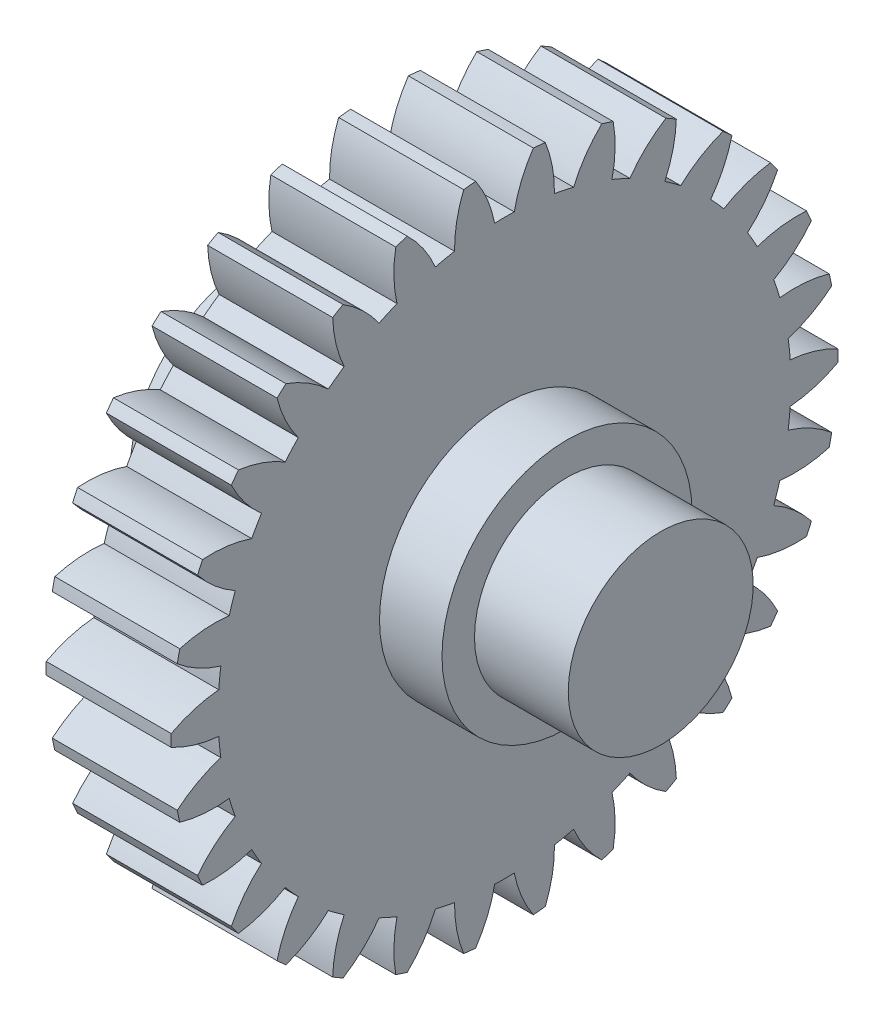
SolidWorks part; units mm, degrees
ref_plane "Plane1" through (0, 0, 0) normal (0, 0, 1) x (1, 0, 0)
ref_plane "Plane2" through (0, 0, 0) normal (0, 1, 0) x (1, 0, 0)
ref_plane "Plane3" through (0, 0, 0) normal (1, 0, 0) x (0, 0, -1)
other "Configuration Table"
sketch "HoldingSke" plane through (0, 0, 0) normal (0, 1, 0) x (1, 0, 0)
  line L0 (0, 0) -> (263.9645, -152.4)
  line L1 (-15, 0) -> (100, 0) construction
  line L2 (0, 0) -> (-2.1039, 2.3779)
  line L3 (0, 0) -> (-11.863, 4.5341)
  line L4 (0, 0) -> (7.479, 4.318)
  line L5 (0, 0) -> (-47.5972, -17.7524)
  line L6 (0, 0) -> (-10.5278, -7.1032)
  line L7 (-2.1039, 2.3779) -> (8.8311, 51.9884)
  line L8 (-76.2, 54.61) -> (-54.9402, 54.61)
  line L9 (-71.009, 38.7566) -> (-53.1078, 45.2721)
  line L10 (-76.2, 71.12) -> (104.1128, 71.12)
  line L11 (0, 0) -> (-12.7, 0)
  line L12 (-76.2, 101.6) -> (-76.1147, 101.6)
  line L13 (24.9733, 27.94) -> (52.9518, 28.4284)
  line L14 (24.9733, 27.94) -> (24.9746, 27.94)
  line L15 (24.9733, 27.94) -> (100.4006, 29.5858)
  circle A0 centre (0, 0) radius 9.525
  circle A1 centre (0, 0) radius 29.1029
  circle A2 centre (0, 0) radius 38.1
  circle A3 centre (0, 0) radius 9.525
  dimension "MHD" = 58.2058
  dimension "Hub_dia" = 76.2
  dimension "Bore" = 19.05
  dimension "MBD" = 19.05
  dimension "Num_teeth" = 30
  dimension "Pitch" = 304.8
  dimension "Overall_len" = 50.8
  dimension "Show_teeth" = 30
  dimension "Thickness" = 12.7
  dimension "OAL" = 50.8014
  dimension "T_dim" = 21.2598
  dimension "Ap" = 20
  dimension "H" = 19.05
  dimension "Pitch_radius" = 180.3128
  dimension "Width" = 12.7
  dimension "Backlash" = 0.0853
  dimension "Addendum_fac" = 1
  dimension "Dedendum_fac" = 1.25
  dimension "Clearance_fac" = 0.25
  dimension "Dedendum_add" = 0.0013
sketch "BasProSke" plane through (0, 0, 0) normal (0, 1, 0) x (1, 0, 0)
  line L0 (-10, 0) -> (60, 0) construction
  line L1 (0, 0) -> (0, 33.8667)
  line L2 (0, 0) -> (12.7, 0)
  line L3 (12.7, 0) -> (12.7, 33.8667)
  line L4 (12.7, 33.8667) -> (0, 33.8667)
  dimension "Thickness" = 12.7
  dimension "Diameter" = 67.7333
revolve "Base-Revolve" add sketch "BasProSke" angle 360 about L0
sketch "TooCutSke" plane through (0, 0, 0) normal (1, 0, 0) x (0, 0, -1)
  line L1 (0, 0) -> (0, 107) construction
  line L2 (0, 0) -> (-1.811, 31.6983) construction
  line L3 (0, 0) -> (-6.63, 63.0805) construction
  line L4 (-1.811, 31.6983) -> (-3.315, 31.5402) construction
  arc A0 (0.9953, 29.0859) -> (-0.9953, 29.0859) centre (0, 0) ccw
  arc A1 (2.9488, 33.7635) -> (-2.9488, 33.7635) centre (0, 0) ccw
  circle A2 centre (0, 0) radius 31.75 construction
  circle A3 centre (0, 0) radius 29.8352 construction
  arc A4 (-0.9953, 29.0859) -> (-2.9488, 33.7635) centre (-13.4553, 26.6289) ccw
  arc A5 (2.9488, 33.7635) -> (0.9953, 29.0859) centre (13.4553, 26.6289) ccw
  dimension "Root_dia" = 58.2058
  dimension "Overcut_dia" = 67.7841
  dimension "Pitch_dia" = 63.5
  dimension "Base_dia" = 59.6705
  dimension "Flank_rad" = 12.7
  dimension "Half_ang" = 6
  dimension "Half_CT" = 1.5123
extrude "ToothCut" cut sketch "TooCutSke" along normal through all
fillet "Breaks" [suppressed] radius 0.0423
fillet "RootFillets" [suppressed] radius 0.5304
pattern_circular "TeethCuts" count 30 every 12 about axis through (-10, 0, 0) along (1, 0, 0) of "ToothCut", "RootFillets", "Breaks"
sketch "HubNeaOneSke" plane through (0, 0, 0) normal (-1, 0, 0) x (0, 0, 1)
  circle A0 centre (0, 0) radius 29.1029
  dimension "Diameter" = 58.2058
extrude "HubNearOne" [suppressed] add sketch "HubNeaOneSke" along normal blind 38.1014
sketch "HubNeaBotSke" plane through (0, 0, 0) normal (-1, 0, 0) x (0, 0, 1)
  circle A0 centre (0, 0) radius 29.1029
  dimension "Diameter" = 58.2058
extrude "HubNearBoth" [suppressed] add sketch "HubNeaBotSke" along normal blind 19.0507
ref_plane "FarPln" through (12.7, 0, 0) normal (1, 0, 0) x (0, 0, -1)
sketch "HubFarSke" plane through (12.7, 0, 0) normal (1, 0, 0) x (0, 0, -1)
  circle A0 centre (0, 0) radius 29.1029
  dimension "Diameter" = 58.2058
extrude "HubFar" [suppressed] add sketch "HubFarSke" along normal blind 19.0507
sketch "Sketch1" plane through (0, 0, 0) normal (-1, 0, 0) x (0, 0, 1)
  circle A0 centre (0, 0) radius 12.7
  circle A1 centre (0, 0) radius 4.953
  dimension "D1" = 9.906
  dimension "D2" = 25.4
extrude "Boss-Extrude2" add sketch "Sketch1" along normal blind 12.7
sketch "Sketch3" plane through (0, 0, 0) normal (0, 1, 0) x (1, 0, 0)
  line L0 (0, 0.9953) -> (0, -0.9953) construction
  line L2 (-12.7, 0) -> (0, 0) construction
  circle A0 centre (-6.35, 0) radius 3.302
  dimension "D1" = 6.604
  dimension "D2" = 6.35
extrude "Cut-Extrude1" cut sketch "Sketch3" along normal through all
sketch "Sketch4" plane through (0, 0, 0) normal (0, 1, 0) x (1, 0, 0)
  line L1 (-3.527, 4.8895) -> (-9.173, 4.8895)
  line L2 (-9.173, 4.8895) -> (-11.9959, 0)
  line L3 (-11.9959, 0) -> (-9.173, -4.8895)
  line L4 (-9.173, -4.8895) -> (-3.527, -4.8895)
  line L5 (-3.527, -4.8895) -> (-0.7041, 0)
  line L6 (-0.7041, 0) -> (-3.527, 4.8895)
  line L7 (0, 12.7) -> (-12.7, 12.7) construction
  circle A0 centre (-6.35, 0) radius 4.8895 construction
  dimension "D1" = 9.779
extrude "Cut-Extrude2" cut sketch "Sketch4" along normal blind 8.255 contours L3 L4 L5 L6 L1 L2
sketch "Sketch5" plane through (12.7, 0, 0) normal (1, 0, 0) x (0, 0, -1)
  circle A0 centre (0, 0) radius 12.7
  dimension "D1" = 25.4
extrude "Boss-Extrude3" add sketch "Sketch5" along normal blind 6.35
sketch "Sketch6" plane through (19.05, 0, 0) normal (1, 0, 0) x (0, 0, -1)
  circle A0 centre (0, 0) radius 9.398
  dimension "D1" = 18.796
extrude "Boss-Extrude4" add sketch "Sketch6" along normal blind 9.525
equation "' \"Pitch@HoldingSke\" = 4"
equation "' \"Num_teeth@HoldingSke\" = 12"
equation "' \"Ap@HoldingSke\" =  20"
equation "' \"Ap@HoldingSke\" = 20"
equation "' \"Width@HoldingSke\" = 0.5"
equation "' \"Hub_dia@HoldingSke\"= 1"
equation "' \"Hub_dia@HoldingSke\" = 1"
equation "' \"Overall_len@HoldingSke\" = 1.0"
equation "' \"Bore@HoldingSke\" = 0.75"
equation "' \"T_dim@HoldingSke\" = 0.85"
equation "' \"Width@KeySke\" = 0.25"
equation "' \"Show_teeth@HoldingSke\" = 13"
equation "' \"Backlash@HoldingSke\" = 0.009"
equation "' \"Addendum_fac@HoldingSke\" = 1.0"
equation "' \"Dedendum_fac@HoldingSke\" = 1.25"
equation "' \"Dedendum_add@HoldingSke\" = 0.00005"
equation "' \"Clearance_fac@HoldingSke\" = 0.25"
equation "' \"Pitch@HoldingSke\" = 0.5"
equation "' \"Num_teeth@HoldingSke\" = 23"
equation "' \"Show_teeth@HoldingSke\" = 23"
equation "' \"Backlash@HoldingSke\" = 0.0375"
equation "\"Overcut_dia@TooCutSke\" = (\"Num_teeth@HoldingSke\" + 2 * \"Addendum_fac@HoldingSke\") / \"Pitch@HoldingSke\" + 0.002"
equation "\"Pitch_dia@TooCutSke\" = \"Num_teeth@HoldingSke\" / \"Pitch@HoldingSke\""
equation "\"Base_dia@TooCutSke\" = \"Num_teeth@HoldingSke\" / \"Pitch@HoldingSke\" * cos((\"Ap@HoldingSke\"  * 3.14159265 / 180))"
equation "\"Root_dia@TooCutSke\" = (\"Num_teeth@HoldingSke\" + 2) / \"Pitch@HoldingSke\" - 2 * (\"Addendum_fac@HoldingSke\" + \"Dedendum_fac@HoldingSke\") / \"Pitch@HoldingSke\" - \"Dedendum_add@HoldingSke\" * 2"
equation "\"Half_ang@TooCutSke\" = 180 / \"Num_teeth@HoldingSke\""
equation "\"Half_CT@TooCutSke\" = \"Num_teeth@HoldingSke\" / \"Pitch@HoldingSke\" * sin((3.14159265 / 2 / \"Num_teeth@HoldingSke\")) / 2 - 7 * \"Backlash@HoldingSke\" / 4"
equation "\"Flank_rad@TooCutSke\" = \"Num_teeth@HoldingSke\" / \"Pitch@HoldingSke\" / 5"
equation "\"Radius@RootFillets\" = \"Clearance_fac@HoldingSke\" / \"Pitch@HoldingSke\" + \"Dedendum_add@HoldingSke\""
equation "\"Break_rad@Breaks\" = 0.02 / \"Pitch@HoldingSke\""
equation "\"Thickness@HoldingSke\" = \"Width@HoldingSke\""
equation "\"OAL@HoldingSke\" = \"Thickness@HoldingSke\""
equation "\"MHD@HoldingSke\" = (\"Num_teeth@HoldingSke\" + 2) / \"Pitch@HoldingSke\" - 2 * (\"Addendum_fac@HoldingSke\" + \"Dedendum_fac@HoldingSke\")  / \"Pitch@HoldingSke\" - \"Dedendum_add@HoldingSke\" * 2"
equation "\"MBD@HoldingSke\" = (\"Num_teeth@HoldingSke\" + 2) / \"Pitch@HoldingSke\" - 2 * (\"Addendum_fac@HoldingSke\" + \"Dedendum_fac@HoldingSke\")  / \"Pitch@HoldingSke\" - \"Dedendum_add@HoldingSke\" * 2 - 0.002"
equation "\"MHD@HoldingSke\" = ((sgn( \"MHD@HoldingSke\" - \"Hub_dia@HoldingSke\" )-1)*( \"MHD@HoldingSke\" - \"Hub_dia@HoldingSke\" ))/-2+ \"Hub_dia@HoldingSke\""
equation "\"MBD@HoldingSke\" = ((sgn( \"MBD@HoldingSke\" - \"Bore@HoldingSke\" )-1)*( \"MBD@HoldingSke\" - \"Bore@HoldingSke\" ))/-2+ \"Bore@HoldingSke\""
equation "\"OAL@HoldingSke\" = ((sgn( \"OAL@HoldingSke\" - \"Overall_len@HoldingSke\" )+1)*( \"OAL@HoldingSke\" - \"Overall_len@HoldingSke\" ))/2 + \"Overall_len@HoldingSke\" + 0.000002"
equation "\"Num_teeth@TeethCuts\" = int( \"Show_teeth@HoldingSke\" ) + 1"
equation "\"Num_teeth@TeethCuts\" = ((sgn( \"Num_teeth@TeethCuts\" - \"Num_teeth@HoldingSke\" )-1)*( \"Num_teeth@TeethCuts\" - \"Num_teeth@HoldingSke\" ))/-2+ \"Num_teeth@HoldingSke\""
equation "\"Num_teeth@TeethCuts\" = ((sgn( \"Num_teeth@TeethCuts\" - 2.0)+1)*( \"Num_teeth@TeethCuts\" - 2.0))/2 +2.0"
equation "\"Angle@TeethCuts\" = 360.0 / \"Num_teeth@HoldingSke\""
equation "\"Diameter@BasProSke\" = (\"Num_teeth@HoldingSke\" + 2 * \"Addendum_fac@HoldingSke\") / \"Pitch@HoldingSke\""
equation "\"Thickness@BasProSke\"  = \"Thickness@HoldingSke\""
equation "' \"Fillet_rad@BasProSke\" =  \"Thickness@HoldingSke\" * 0.05"
equation "' \"Fillet_rad@BasProSke\" = \"Thickness@HoldingSke\" * 0.05"
equation "\"MHD@HoldingSke\" = ((sgn( \"MHD@HoldingSke\" - \"Root_dia@TooCutSke\" )-1)*( \"MHD@HoldingSke\" - \"Root_dia@TooCutSke\" ))/-2+ \"Root_dia@TooCutSke\""
equation "\"Diameter@HubNeaOneSke\" = \"MHD@HoldingSke\""
equation "\"Length@HubNearOne\" = \"OAL@HoldingSke\" - \"Thickness@BasProSke\""
equation "\"Diameter@HubNeaBotSke\" = \"MHD@HoldingSke\""
equation "\"Length@HubNearBoth\" = ( \"OAL@HoldingSke\" - \"Thickness@BasProSke\" ) / 2.0"
equation "\"Thickness@FarPln\" = \"Thickness@BasProSke\""
equation "\"Diameter@HubFarSke\" = \"MHD@HoldingSke\""
equation "\"Length@HubFar\" = ( \"OAL@HoldingSke\" - \"Thickness@BasProSke\" ) / 2.0"
equation "\"Diameter@BorSke\" = \"MBD@HoldingSke\""
equation "\"D1\" = \"OAL@HoldingSke\" * 2.0"
equation "\"Offset@KeySke\" = \"T_dim@HoldingSke\" - \"MBD@HoldingSke\" / 2.0"
